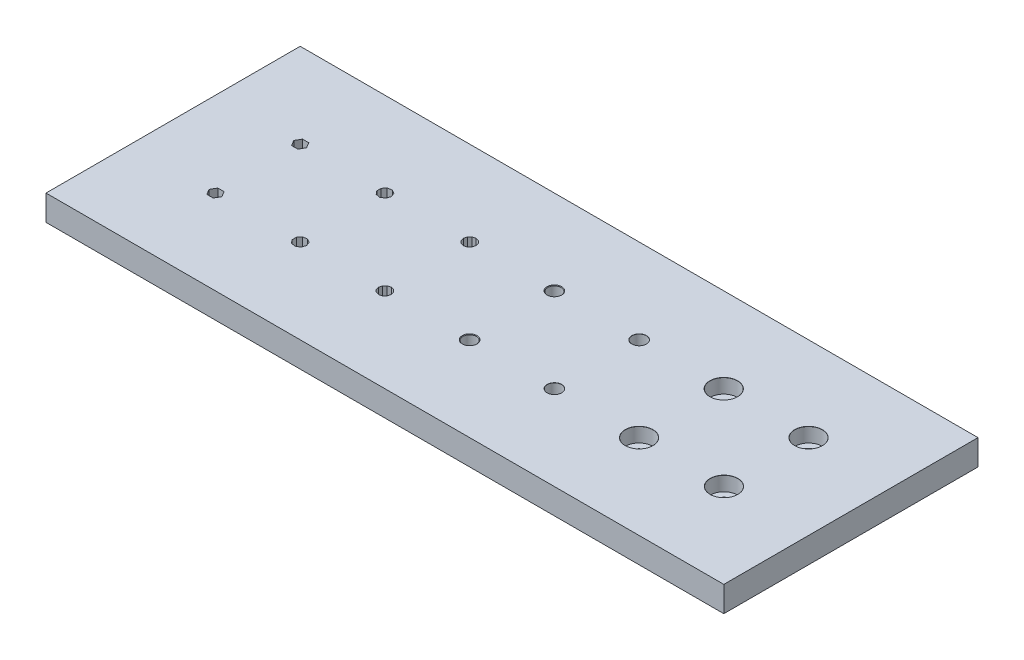
SolidWorks part; units mm, degrees
ref_plane "Front Plane" through (0, 0, 0) normal (0, 0, 1) x (1, 0, 0)
ref_plane "Top Plane" through (0, 0, 0) normal (0, 1, 0) x (1, 0, 0)
ref_plane "Right Plane" through (0, 0, 0) normal (1, 0, 0) x (0, 0, -1)
sketch "Sketch1" plane through (0, 0, 0) normal (0, 1, 0) x (1, 0, 0)
  line L1 (0, 0) -> (160, 0)
  line L2 (0, 0) -> (0, 60)
  line L3 (0, 60) -> (160, 60)
  line L4 (160, 0) -> (160, 60)
extrude "Boss-Extrude1" add sketch "Sketch1" along normal blind 6
sketch "Sketch2" plane through (0, 6, 0) normal (0, 1, 0) x (1, 0, 0)
  line L0 (0, 0) -> (0, 20)
  line L1 (0, 60) -> (0, 0) construction
  line L2 (0, 20) -> (160, 20)
  line L3 (160, 0) -> (160, 60) construction
  line L4 (160, 20) -> (160, 40)
  line L5 (160, 40) -> (0, 40)
  line L6 (0, 20) -> (20, 20)
  line L7 (20, 20) -> (20, 40)
  line L9 (61.4998, 40) -> (61.2989, 40.7499)
  line L10 (61.2989, 40.7499) -> (60.7499, 41.2989)
  line L11 (60.7499, 41.2989) -> (60, 41.4998)
  line L12 (60, 41.4998) -> (59.2501, 41.2989)
  line L13 (59.2501, 41.2989) -> (58.7011, 40.7499)
  line L14 (58.7011, 40.7499) -> (58.5002, 40)
  line L15 (58.5002, 40) -> (58.7011, 39.2501)
  line L16 (58.7011, 39.2501) -> (59.2501, 38.7011)
  line L17 (59.2501, 38.7011) -> (60, 38.5002)
  line L18 (60, 38.5002) -> (60.7499, 38.7011)
  line L19 (60.7499, 38.7011) -> (61.2989, 39.2501)
  line L20 (61.2989, 39.2501) -> (61.4998, 40)
  line L21 (61.4998, 20) -> (61.2989, 20.7499)
  line L22 (61.2989, 20.7499) -> (60.7499, 21.2989)
  line L23 (60.7499, 21.2989) -> (60, 21.4998)
  line L24 (60, 21.4998) -> (59.2501, 21.2989)
  line L25 (59.2501, 21.2989) -> (58.7011, 20.7499)
  line L26 (58.7011, 20.7499) -> (58.5002, 20)
  line L27 (58.5002, 20) -> (58.7011, 19.2501)
  line L28 (58.7011, 19.2501) -> (59.2501, 18.7011)
  line L29 (59.2501, 18.7011) -> (60, 18.5002)
  line L30 (60, 18.5002) -> (60.7499, 18.7011)
  line L31 (60.7499, 18.7011) -> (61.2989, 19.2501)
  line L32 (61.2989, 19.2501) -> (61.4998, 20)
  line L33 (41.4998, 40) -> (41.1489, 40.9641)
  line L34 (41.1489, 40.9641) -> (40.2604, 41.477)
  line L35 (40.2604, 41.477) -> (39.2501, 41.2989)
  line L36 (39.2501, 41.2989) -> (38.5906, 40.513)
  line L37 (38.5906, 40.513) -> (38.5906, 39.487)
  line L38 (38.5906, 39.487) -> (39.2501, 38.7011)
  line L39 (39.2501, 38.7011) -> (40.2604, 38.523)
  line L40 (40.2604, 38.523) -> (41.1489, 39.0359)
  line L41 (41.1489, 39.0359) -> (41.4998, 40)
  line L42 (41.6274, 20) -> (40.8137, 21.4094)
  line L43 (40.8137, 21.4094) -> (39.1863, 21.4094)
  line L44 (39.1863, 21.4094) -> (38.3726, 20)
  line L45 (38.3726, 20) -> (39.1863, 18.5906)
  line L46 (39.1863, 18.5906) -> (40.8137, 18.5906)
  line L47 (40.8137, 18.5906) -> (41.6274, 20)
  line L48 (21.5002, 40) -> (20.7501, 41.2992)
  line L49 (20.7501, 41.2992) -> (19.2499, 41.2992)
  line L50 (19.2499, 41.2992) -> (18.4998, 40)
  line L51 (18.4998, 40) -> (19.2499, 38.7008)
  line L52 (19.2499, 38.7008) -> (20.7501, 38.7008)
  line L53 (20.7501, 38.7008) -> (21.5002, 40)
  line L54 (21.5002, 20) -> (20.7501, 21.2992)
  line L55 (20.7501, 21.2992) -> (19.2499, 21.2992)
  line L56 (19.2499, 21.2992) -> (18.4998, 20)
  line L57 (18.4998, 20) -> (19.2499, 18.7008)
  line L58 (19.2499, 18.7008) -> (20.7501, 18.7008)
  line L59 (20.7501, 18.7008) -> (21.5002, 20)
  circle A0 centre (20, 40) radius 1.5
  circle A1 centre (40, 40) radius 1.5
  circle A2 centre (60, 40) radius 1.5
  circle A3 centre (80, 40) radius 1.5
  circle A4 centre (100, 40) radius 1.5
  circle A5 centre (120, 40) radius 1.5
  circle A6 centre (140, 40) radius 1.5
  circle A7 centre (40, 20) radius 1.5
  circle A8 centre (60, 20) radius 1.5
  circle A9 centre (80, 20) radius 1.5
  circle A10 centre (100, 20) radius 1.5
  circle A11 centre (120, 20) radius 1.5
  circle A12 centre (140, 20) radius 1.5
  circle A13 centre (20, 20) radius 1.5
  circle A14 centre (60, 40) radius 1.4487 construction
  circle A15 centre (60, 20) radius 1.4487 construction
  circle A16 centre (40, 40) radius 1.4094 construction
  circle A17 centre (40, 20) radius 1.4094 construction
  circle A18 centre (20, 40) radius 1.2992 construction
  circle A19 centre (20, 20) radius 1.2992 construction
  point P13 (0, 0)
  point P97 (0, 0)
  point P98 (0, 0)
  point P99 (0, 0)
  point P100 (0, 0)
  dimension "D1" = 7
  dimension "D2" = 2
sketch "Sketch5" plane through (0, 6, 0) normal (0, 1, 0) x (1, 0, 0)
  point P0 (139.9925, 20.043)
hole_wizard "CBORE for M3 Hex Socket Head Cap Screw1" positions "Sketch5" profile "Sketch4" counterbore size "M3" standard "ISO" end condition through all
sketch "Sketch4" plane through (139.9925, 6, -20.043) normal (1, 0, 0) x (0, 0, 1)
  line L0 (0, 0) -> (0, 6)
  line L1 (0, 6) -> (1.7, 6)
  line L3 (1.7, 6) -> (1.7, 3.4)
  line L4 (3.25, 3.4) -> (1.7, 3.4)
  line L5 (3.25, 3.4) -> (3.25, 0.025)
  line L6 (3.25, 0.025) -> (3.275, 0)
  line L7 (3.275, 0) -> (0, 0)
  line L8 (-3.25, 0.025) -> (-3.275, 0) construction
  line L11 (0, -6.35) -> (0, 107.95) construction
  dimension "Thru Hole Dia." = 3.4
  dimension "Thru Hole Depth" = 6
  dimension "C'Bore Dia." = 6.5
  dimension "C'Bore Depth" = 3.4
  dimension "Near C'Sink Dia." = 6.55
  dimension "Near C'Sink Angle" = 90
sketch "Sketch8" plane through (0, 6, 0) normal (0, 1, 0) x (1, 0, 0)
  point P0 (140.0041, 39.9929)
hole_wizard "CBORE for M3 Hex Socket Head Cap Screw2" positions "Sketch8" profile "Sketch7" counterbore size "M3" standard "ISO" end condition through all
sketch "Sketch7" plane through (140.0041, 6, -39.9929) normal (1, 0, 0) x (0, 0, 1)
  line L0 (0, 0) -> (0, 6)
  line L1 (0, 6) -> (1.7, 6)
  line L3 (1.7, 6) -> (1.7, 3.4)
  line L4 (3.25, 3.4) -> (1.7, 3.4)
  line L5 (3.25, 3.4) -> (3.25, 0.025)
  line L6 (3.25, 0.025) -> (3.275, 0)
  line L7 (3.275, 0) -> (0, 0)
  line L8 (-3.25, 0.025) -> (-3.275, 0) construction
  line L11 (0, -6.35) -> (0, 107.95) construction
  dimension "Thru Hole Dia." = 3.4
  dimension "Thru Hole Depth" = 6
  dimension "C'Bore Dia." = 6.5
  dimension "C'Bore Depth" = 3.4
  dimension "Near C'Sink Dia." = 6.55
  dimension "Near C'Sink Angle" = 90
sketch "Sketch11" plane through (0, 6, 0) normal (0, 1, 0) x (1, 0, 0)
  point P0 (120.0002, 39.9849)
hole_wizard "CBORE for M3 Hex Socket Head Cap Screw3" positions "Sketch11" profile "Sketch10" counterbore size "M3" standard "ISO" end condition through all
sketch "Sketch10" plane through (120.0002, 6, -39.9849) normal (1, 0, 0) x (0, 0, 1)
  line L0 (0, 0) -> (0, 6)
  line L1 (0, 6) -> (1.6, 6)
  line L3 (1.6, 6) -> (1.6, 3.4)
  line L4 (3.25, 3.4) -> (1.6, 3.4)
  line L5 (3.25, 3.4) -> (3.25, 0.025)
  line L6 (3.25, 0.025) -> (3.275, 0)
  line L7 (3.275, 0) -> (0, 0)
  line L8 (-3.25, 0.025) -> (-3.275, 0) construction
  line L11 (0, -6.35) -> (0, 107.95) construction
  dimension "Thru Hole Dia." = 3.2
  dimension "Thru Hole Depth" = 6
  dimension "C'Bore Dia." = 6.5
  dimension "C'Bore Depth" = 3.4
  dimension "Near C'Sink Dia." = 6.55
  dimension "Near C'Sink Angle" = 90
sketch "Sketch14" plane through (0, 6, 0) normal (0, 1, 0) x (1, 0, 0)
  point P0 (119.9973, 19.9993)
hole_wizard "CBORE for M3 Hex Socket Head Cap Screw4" positions "Sketch14" profile "Sketch13" counterbore size "M3" standard "ISO" end condition through all
sketch "Sketch13" plane through (119.9973, 6, -19.9993) normal (1, 0, 0) x (0, 0, 1)
  line L0 (0, 0) -> (0, 6)
  line L1 (0, 6) -> (1.6, 6)
  line L3 (1.6, 6) -> (1.6, 3.4)
  line L4 (3.25, 3.4) -> (1.6, 3.4)
  line L5 (3.25, 3.4) -> (3.25, 0.025)
  line L6 (3.25, 0.025) -> (3.275, 0)
  line L7 (3.275, 0) -> (0, 0)
  line L8 (-3.25, 0.025) -> (-3.275, 0) construction
  line L11 (0, -6.35) -> (0, 107.95) construction
  dimension "Thru Hole Dia." = 3.2
  dimension "Thru Hole Depth" = 6
  dimension "C'Bore Dia." = 6.5
  dimension "C'Bore Depth" = 3.4
  dimension "Near C'Sink Dia." = 6.55
  dimension "Near C'Sink Angle" = 90
sketch "Sketch17" plane through (0, 6, 0) normal (0, 1, 0) x (1, 0, 0)
  point P0 (100.0197, 40.0026)
hole_wizard "M3 Clearance Hole1" positions "Sketch17" profile "Sketch16" hole size "M3" standard "ISO" end condition through all
sketch "Sketch16" plane through (100.0197, 6, -40.0026) normal (1, 0, 0) x (0, 0, 1)
  line L0 (0, 0) -> (0, 6)
  line L1 (0, 6) -> (1.7, 6)
  line L2 (1.7, 6) -> (1.7, 0.025)
  line L3 (1.7, 0.025) -> (1.725, 0)
  line L5 (1.725, 0) -> (0, 0)
  line L6 (-1.7, 0.025) -> (-1.725, 0) construction
  line L11 (0, -6.35) -> (0, 107.95) construction
  dimension "Thru Hole Dia." = 3.4
  dimension "Thru Hole Depth" = 6
  dimension "Near C'Sink Dia." = 3.45
  dimension "Near C'Sink Angle" = 90
sketch "Sketch20" plane through (0, 6, 0) normal (0, 1, 0) x (1, 0, 0)
  point P0 (99.9903, 20.0038)
sketch "Sketch23" plane through (0, 6, 0) normal (0, 1, 0) x (1, 0, 0)
  point P0 (99.9939, 20.016)
hole_wizard "M3 Clearance Hole3" positions "Sketch23" profile "Sketch22" hole size "M3" standard "ISO" end condition through all
sketch "Sketch22" plane through (99.9939, 6, -20.016) normal (1, 0, 0) x (0, 0, 1)
  line L0 (0, 0) -> (0, 6)
  line L1 (0, 6) -> (1.7, 6)
  line L2 (1.7, 6) -> (1.7, 0.025)
  line L3 (1.7, 0.025) -> (1.725, 0)
  line L5 (1.725, 0) -> (0, 0)
  line L6 (-1.7, 0.025) -> (-1.725, 0) construction
  line L11 (0, -6.35) -> (0, 107.95) construction
  dimension "Thru Hole Dia." = 3.4
  dimension "Thru Hole Depth" = 6
  dimension "Near C'Sink Dia." = 3.45
  dimension "Near C'Sink Angle" = 90
sketch "Sketch26" plane through (0, 6, 0) normal (0, 1, 0) x (1, 0, 0)
  point P0 (79.9972, 40.0052)
hole_wizard "M3 Clearance Hole4" positions "Sketch26" profile "Sketch25" hole size "M3" standard "ISO" end condition through all
sketch "Sketch25" plane through (79.9972, 6, -40.0052) normal (1, 0, 0) x (0, 0, 1)
  line L0 (0, 0) -> (0, 6)
  line L1 (0, 6) -> (1.6, 6)
  line L2 (1.6, 6) -> (1.6, 0.125)
  line L3 (1.6, 0.125) -> (1.725, 0)
  line L5 (1.725, 0) -> (0, 0)
  line L6 (-1.6, 0.125) -> (-1.725, 0) construction
  line L11 (0, -6.35) -> (0, 107.95) construction
  dimension "Thru Hole Dia." = 3.2
  dimension "Thru Hole Depth" = 6
  dimension "Near C'Sink Dia." = 3.45
  dimension "Near C'Sink Angle" = 90
sketch "Sketch29" plane through (0, 6, 0) normal (0, 1, 0) x (1, 0, 0)
  point P0 (79.9915, 20.0041)
hole_wizard "M3 Clearance Hole5" positions "Sketch29" profile "Sketch28" hole size "M3" standard "ISO" end condition through all
sketch "Sketch28" plane through (79.9915, 6, -20.0041) normal (1, 0, 0) x (0, 0, 1)
  line L0 (0, 0) -> (0, 6)
  line L1 (0, 6) -> (1.6, 6)
  line L2 (1.6, 6) -> (1.6, 0.125)
  line L3 (1.6, 0.125) -> (1.725, 0)
  line L5 (1.725, 0) -> (0, 0)
  line L6 (-1.6, 0.125) -> (-1.725, 0) construction
  line L11 (0, -6.35) -> (0, 107.95) construction
  dimension "Thru Hole Dia." = 3.2
  dimension "Thru Hole Depth" = 6
  dimension "Near C'Sink Dia." = 3.45
  dimension "Near C'Sink Angle" = 90
extrude "Cut-Extrude3" cut sketch "Sketch2" against normal through all contours L31 L32 L21 L22 L23 L24 L25 L26 L27 L28 L29 L30
sketch "Sketch35" plane through (0, 6, 0) normal (0, 1, 0) x (1, 0, 0)
  line L0 (0, 0) -> (0, 20)
  line L1 (0, 60) -> (0, 0) construction
  line L2 (0, 20) -> (20, 20)
  line L3 (20, 20) -> (40, 20)
  line L4 (40, 20) -> (40, 40)
  line L5 (40, 40) -> (20, 40)
  line L6 (40, 40) -> (60, 40)
  line L8 (58.5, 40) -> (58.701, 39.25)
  line L9 (58.701, 39.25) -> (59.25, 38.701)
  line L10 (59.25, 38.701) -> (60, 38.5)
  line L11 (60, 38.5) -> (60.75, 38.701)
  line L12 (60.75, 38.701) -> (61.299, 39.25)
  line L13 (61.299, 39.25) -> (61.5, 40)
  line L14 (61.5, 40) -> (61.299, 40.75)
  line L15 (61.299, 40.75) -> (60.75, 41.299)
  line L16 (60.75, 41.299) -> (60, 41.5)
  line L17 (60, 41.5) -> (59.25, 41.299)
  line L18 (59.25, 41.299) -> (58.701, 40.75)
  line L19 (58.701, 40.75) -> (58.5, 40)
  circle A0 centre (40, 20) radius 1.5
  circle A1 centre (40, 40) radius 1.5
  circle A2 centre (20, 40) radius 1.5
  circle A3 centre (20, 20) radius 1.5
  circle A4 centre (60, 40) radius 1.5
  circle A5 centre (60, 40) radius 1.4489 construction
extrude "Cut-Extrude4" cut sketch "Sketch35" against normal through all
sketch "Sketch36" plane through (0, 6, 0) normal (0, 1, 0) x (1, 0, 0)
  line L0 (0, 0) -> (0, 20)
  line L1 (0, 60) -> (0, 0) construction
  line L2 (0, 20) -> (40, 20)
  line L4 (41.5, 20) -> (41.1491, 20.9642)
  line L5 (41.1491, 20.9642) -> (40.2605, 21.4772)
  line L6 (40.2605, 21.4772) -> (39.25, 21.299)
  line L7 (39.25, 21.299) -> (38.5905, 20.513)
  line L8 (38.5905, 20.513) -> (38.5905, 19.487)
  line L9 (38.5905, 19.487) -> (39.25, 18.701)
  line L10 (39.25, 18.701) -> (40.2605, 18.5228)
  line L11 (40.2605, 18.5228) -> (41.1491, 19.0358)
  line L12 (41.1491, 19.0358) -> (41.5, 20)
  circle A0 centre (40, 20) radius 1.5
  circle A1 centre (40, 20) radius 1.4095 construction
extrude "Cut-Extrude5" cut sketch "Sketch36" against normal through all
sketch "Sketch37" plane through (0, 6, 0) normal (0, 1, 0) x (1, 0, 0)
  line L0 (0, 0) -> (0, 40)
  line L1 (0, 60) -> (0, 0) construction
  line L2 (0, 40) -> (40, 40)
  line L4 (41.5, 40) -> (41.1491, 40.9642)
  line L5 (41.1491, 40.9642) -> (40.2605, 41.4772)
  line L6 (40.2605, 41.4772) -> (39.25, 41.299)
  line L7 (39.25, 41.299) -> (38.5905, 40.513)
  line L8 (38.5905, 40.513) -> (38.5905, 39.487)
  line L9 (38.5905, 39.487) -> (39.25, 38.701)
  line L10 (39.25, 38.701) -> (40.2605, 38.5228)
  line L11 (40.2605, 38.5228) -> (41.1491, 39.0358)
  line L12 (41.1491, 39.0358) -> (41.5, 40)
  circle A0 centre (40, 40) radius 1.5
  circle A1 centre (40, 40) radius 1.4095 construction
extrude "Cut-Extrude6" cut sketch "Sketch37" against normal through all
sketch "Sketch38" plane through (0, 6, 0) normal (0, 1, 0) x (1, 0, 0)
  line L0 (0, 0) -> (0, 20)
  line L1 (0, 60) -> (0, 0) construction
  line L2 (0, 20) -> (20, 20)
  line L4 (21.5, 20) -> (20.75, 21.299)
  line L5 (20.75, 21.299) -> (19.25, 21.299)
  line L6 (19.25, 21.299) -> (18.5, 20)
  line L7 (18.5, 20) -> (19.25, 18.701)
  line L8 (19.25, 18.701) -> (20.75, 18.701)
  line L9 (20.75, 18.701) -> (21.5, 20)
  circle A0 centre (20, 20) radius 1.5
  circle A1 centre (20, 20) radius 1.299 construction
extrude "Cut-Extrude7" cut sketch "Sketch38" against normal through all
sketch "Sketch39" plane through (0, 6, 0) normal (0, 1, 0) x (1, 0, 0)
  line L0 (0, 0) -> (0, 40)
  line L1 (0, 60) -> (0, 0) construction
  line L2 (0, 40) -> (20, 40)
  line L4 (21.5, 40) -> (20.75, 41.299)
  line L5 (20.75, 41.299) -> (19.25, 41.299)
  line L6 (19.25, 41.299) -> (18.5, 40)
  line L7 (18.5, 40) -> (19.25, 38.701)
  line L8 (19.25, 38.701) -> (20.75, 38.701)
  line L9 (20.75, 38.701) -> (21.5, 40)
  circle A0 centre (20, 40) radius 1.5
  circle A1 centre (20, 40) radius 1.299 construction
extrude "Cut-Extrude8" cut sketch "Sketch39" against normal through all
